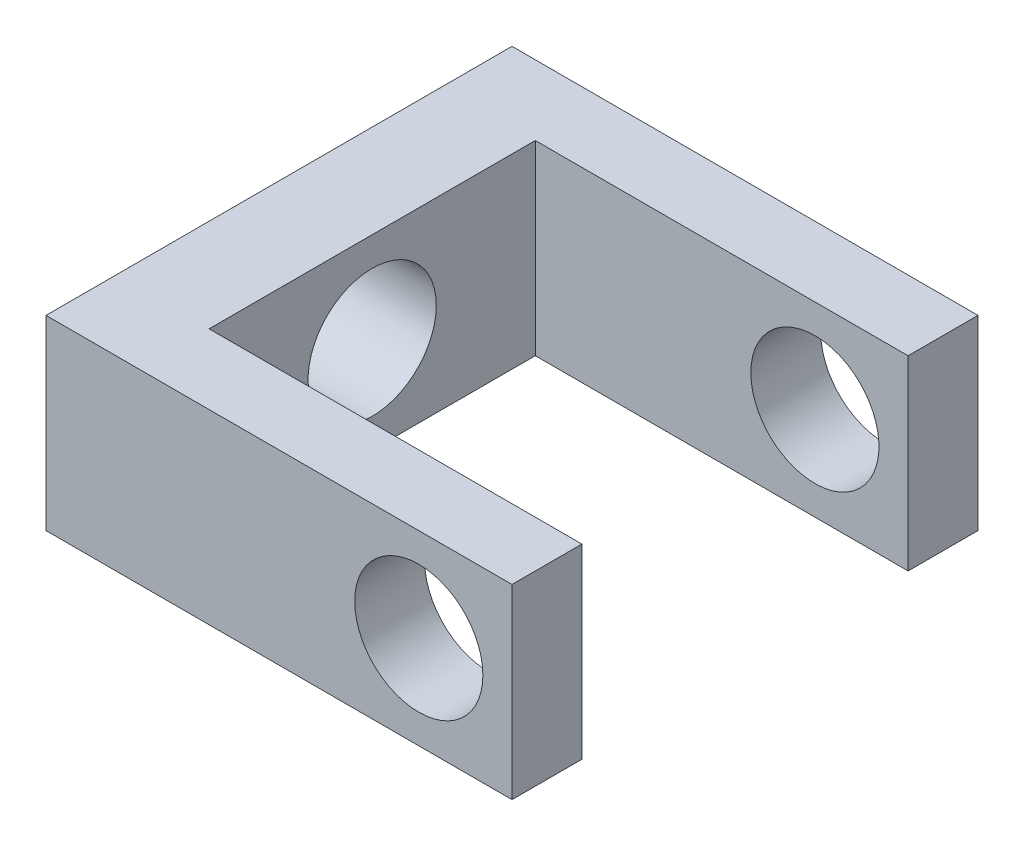
SolidWorks part; units mm, degrees
ref_plane "Front Plane" through (0, 0, 0) normal (0, 0, 1) x (1, 0, 0)
ref_plane "Top Plane" through (0, 0, 0) normal (0, 1, 0) x (1, 0, 0)
ref_plane "Right Plane" through (0, 0, 0) normal (1, 0, 0) x (0, 0, -1)
sketch "Sketch1" plane through (0, 0, 0) normal (0, 0, 1) x (1, 0, 0)
  line L0 (0, 0) -> (10, 0) construction
  line L1 (-10, -4) -> (10, -4)
  line L2 (-10, -4) -> (-10, 4)
  line L3 (-10, 4) -> (10, 4)
  line L4 (10, -4) -> (10, 4)
  line L5 (-10, -4) -> (10, 4) construction
  line L6 (-10, 4) -> (10, -4) construction
  circle A0 centre (6, 0) radius 2.75
  circle A1 centre (6, 0) radius 7.5 construction
  point P0 (0, 0)
  point P8 (6, 0)
  point P11 (4.137, 0)
  point P12 (4.461, 0)
  point P13 (2.5114, 0)
  point P14 (0, 0)
  point P15 (0, 0)
  dimension "D1" = 5.5
  dimension "D2" = 15
  dimension "D3" = 8
  dimension "D4" = 20
  dimension "D5" = 4
extrude "Boss-Extrude1" add sketch "Sketch1" along normal blind 20
sketch "Sketch2" plane through (10, 0, 0) normal (1, 0, 0) x (0, 0, -1)
  line L0 (-20, 0) -> (0, 0) construction
  line L1 (-10, 4) -> (-10, -4) construction
  line L2 (-17, 4) -> (-20, 4) construction
  line L3 (-17, -4) -> (-3, -4)
  line L4 (0, -4) -> (0, 4)
  line L5 (0, 4) -> (-20, 4)
  line L6 (-20, 4) -> (-20, -4)
  line L7 (-20, -4) -> (0, -4)
  line L8 (0, 0) -> (0, 4) construction
  line L9 (-3, 4) -> (-17, 4)
  line L10 (-20, 0) -> (-20, -4) construction
  line L11 (-17, -4) -> (-3, -4)
  line L12 (-17, -4) -> (-17, 4)
  line L13 (-17, 4) -> (-3, 4)
  line L14 (-3, -4) -> (-3, 4)
  line L15 (-17, -4) -> (-3, 4) construction
  line L16 (-17, 4) -> (-3, -4) construction
  line L17 (-20, 4) -> (-20, 0) construction
  line L18 (-20, -4) -> (-17, -4) construction
  line L19 (-3, -4) -> (0, -4) construction
  line L20 (0, -4) -> (0, 0) construction
  line L21 (0, 4) -> (-3, 4) construction
  point P8 (-10, 0)
  point P9 (-10, 0)
  line M8 (0, 4) -> (-20, 4)
  line M10 (-20, -4) -> (0, -4)
  dimension "D2" = 14
  dimension "D1" = 0
extrude "Cut-Extrude1" cut sketch "Sketch2" against normal blind 16 contours L14 L12 M10 M8
sketch "Sketch3" plane through (-6, 0, 0) normal (1, 0, 0) x (0, 0, -1)
  line L0 (-17, 4) -> (-3, -4) construction
  line L1 (-3, 4) -> (-17, -4) construction
  line L4 (-17, -4) -> (-3, -4)
  line L5 (-3, -4) -> (-3, 4)
  line L6 (-3, 4) -> (-17, 4)
  line L7 (-17, 4) -> (-17, -4)
  line L8 (-17, -4) -> (-3, -4) construction
  line L9 (-3, -4) -> (-3, 4) construction
  line L10 (-3, 4) -> (-17, 4) construction
  line L11 (-17, 4) -> (-17, -4) construction
  circle A0 centre (-10, 0) radius 2.75
  point P2 (-10, 0)
  dimension "D2" = 5.5
  dimension "D1" = 0
extrude "Cut-Extrude2" cut sketch "Sketch3" against normal through all
